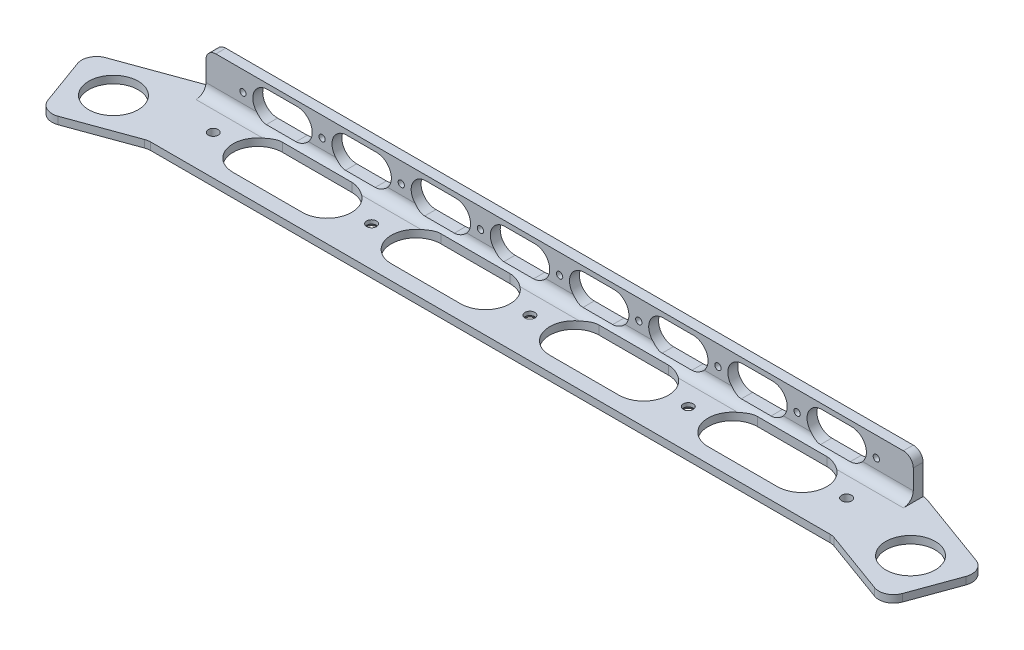
SolidWorks part; units mm, degrees
material "6061-T6 (SS)"
ref_plane "Front Plane" through (0, 0, 0) normal (0, 0, 1) x (1, 0, 0)
ref_plane "Top Plane" through (0, 0, 0) normal (0, 1, 0) x (1, 0, 0)
ref_plane "Right Plane" through (0, 0, 0) normal (1, 0, 0) x (0, 0, -1)
sketch "Sketch1" plane through (0, 0, 0) normal (0, 1, 0) x (1, 0, 0)
  line L0 (-230.1782, 50.2256) -> (-279.3199, 32.3395)
  line L1 (-217.9631, 0) -> (217.9631, 0)
  line L2 (226.9205, 50.8) -> (-226.9205, 50.8)
  line L3 (261.9453, -15.3969) -> (221.2208, -0.5744)
  line L4 (285.0127, 20.1311) -> (274.1536, -9.7041)
  line L5 (-285.0127, 20.1311) -> (-274.1536, -9.7041)
  line L6 (-261.9453, -15.3969) -> (-221.2208, -0.5744)
  line L7 (0, 50.8) -> (0, 0) construction
  line L8 (230.1782, 50.2256) -> (279.3199, 32.3395)
  arc A0 (-221.2208, -0.5744) -> (-217.9631, 0) centre (-217.9631, -9.525) cw
  arc A1 (-230.1782, 50.2256) -> (-226.9205, 50.8) centre (-226.9205, 41.275) cw
  arc A2 (-279.3199, 32.3395) -> (-285.0127, 20.1311) centre (-276.0622, 23.3889) ccw
  arc A3 (-274.1536, -9.7041) -> (-261.9453, -15.3969) centre (-265.203, -6.4464) ccw
  arc A4 (274.1536, -9.7041) -> (261.9453, -15.3969) centre (265.203, -6.4464) cw
  arc A5 (279.3199, 32.3395) -> (285.0127, 20.1311) centre (276.0622, 23.3889) cw
  arc A6 (230.1782, 50.2256) -> (226.9205, 50.8) centre (226.9205, 41.275) ccw
  arc A7 (221.2208, -0.5744) -> (217.9631, 0) centre (217.9631, -9.525) ccw
  point P11 (-228.6, 50.8)
  point P29 (228.6, 50.8)
  dimension "D3" = 9.525
  dimension "D1" = 50.8
  dimension "D2" = 20
  dimension "D4" = 63.5
  dimension "D5" = 228.6
  dimension "D6" = 50.8
extrude "Boss-Extrude1" add sketch "Sketch1" along normal blind 4.7752
sketch "Sketch2" plane through (0, 4.7752, 0) normal (0, 1, 0) x (1, 0, 0)
  line L0 (0, 50.8) -> (0, 0) construction
  line L3 (226.9205, 50.8) -> (-226.9205, 50.8) construction
  circle A0 centre (0, 25.4) radius 3.175
  circle A1 centre (-101.6, 25.4) radius 3.175
  circle A2 centre (101.6, 25.4) radius 3.175
  circle A3 centre (203.2, 25.4) radius 3.175
  circle A4 centre (-203.2, 25.4) radius 3.175
  point P4 (0, 25.4)
  dimension "D1" = 101.6
  dimension "D2" = 101.6
  dimension "D4" = 6.35
  dimension "D3" = 101.6
  dimension "D5" = 101.6
extrude "Cut-Extrude1" cut sketch "Sketch2" against normal through all
sketch "Sketch3" plane through (0, 4.7752, 0) normal (0, 1, 0) x (1, 0, 0)
  line L1 (-226.9205, 50.8) -> (226.9205, 50.8)
  line L2 (-226.9205, 50.8) -> (-226.9205, 44.45)
  line L3 (-226.9205, 44.45) -> (226.9205, 44.45)
  line L4 (226.9205, 50.8) -> (226.9205, 44.45)
  dimension "D1" = 6.35
extrude "Boss-Extrude2" add sketch "Sketch3" along normal blind 25.4
fillet "Fillet1" radius 6.35 1 edges at (0, 4.7752, -44.45)
sketch "Sketch4" plane through (0, 0, -50.8) normal (0, 0, -1) x (-1, 0, 0)
  line L0 (-226.9205, 17.4625) -> (226.9205, 17.4625) construction
  line L1 (-226.9205, 30.1752) -> (-226.9205, 4.7752) construction
  line L2 (226.9205, 30.1752) -> (226.9205, 4.7752) construction
  line L3 (-226.9205, 0) -> (226.9205, 0) construction
  dimension "D1" = 17.4625
hole_wizard "#10-32 Tapped Hole1" positions "Sketch6" profile "Sketch7" tap size "#10-32" standard "Ansi Inch" end condition up to next
sketch "Sketch6" plane through (0, 0, -50.8) normal (0, 0, -1) x (-1, 0, 0)
  line L0 (-226.9205, 17.4625) -> (226.9205, 17.4625) construction
  point P0 (0, 17.4625)
sketch "Sketch7" plane through (0, 17.4625, -50.8) normal (1, 0, 0) x (0, 1, 0)
  line L0 (0, 0) -> (0, 66.7714)
  line L1 (0, 66.7714) -> (2.0193, 66.7714)
  line L2 (2.0193, 66.7714) -> (2.0193, 0)
  line L5 (2.0193, 0) -> (0, 0)
  line L11 (0, -6.35) -> (0, 107.95) construction
  dimension "Thru Tap Drill Dia." = 4.0386
  dimension "Thru Tap Drill Depth" = 66.7714
cosmetic thread "Hole Thread1"
pattern_linear "LPattern1" count 5 spacing 50.8 along (-1, 0, 0) count 5 spacing 50.8 along (1, 0, 0) of "#10-32 Tapped Hole1"
sketch "Sketch9" plane through (0, 0, -50.8) normal (0, 0, -1) x (-1, 0, 0)
  line L0 (-226.9205, 17.4625) -> (226.9205, 17.4625) construction
  line L1 (-226.9205, 30.1752) -> (-226.9205, 4.7752) construction
  line L2 (226.9205, 30.1752) -> (226.9205, 4.7752) construction
  line L3 (-226.9205, 0) -> (226.9205, 0) construction
  line L4 (168.275, 17.4625) -> (187.325, 17.4625) construction
  line L5 (168.275, 26.9875) -> (187.325, 26.9875)
  line L6 (168.275, 7.9375) -> (187.325, 7.9375)
  arc A0 (168.275, 26.9875) -> (168.275, 7.9375) centre (168.275, 17.4625) ccw
  arc A1 (187.325, 7.9375) -> (187.325, 26.9875) centre (187.325, 17.4625) ccw
  circle A2 centre (203.2, 17.4625) radius 2.0193 construction
  point P10 (177.8, 17.4625)
  dimension "D3" = 19.05
  dimension "D2" = 9.525
  dimension "D1" = 17.4625
  dimension "D4" = 25.4
extrude "Cut-Extrude2" cut sketch "Sketch9" against normal up to next
pattern_linear "LPattern2" count 8 spacing 50.8 along (1, 0, 0) of "Cut-Extrude2"
fillet "Fillet2" radius 6.35 2 edges at (226.9205, 30.1752, -47.625) (-226.9205, 30.1752, -47.625)
sketch "Sketch10" plane through (0, 0, 0) normal (0, -1, 0) x (1, 0, 0)
  line L0 (-261.9453, 15.3969) -> (-221.2208, 0.5744) construction
  line L1 (-285.0127, -20.1311) -> (-274.1536, 9.7041) construction
  line L2 (-217.9631, 0) -> (217.9631, 0) construction
  circle A0 centre (-255.715, -13.9008) radius 15.875
  circle A1 centre (-174.625, -25.4) radius 15.875
  circle A3 centre (-130.175, -25.4) radius 15.875
  circle A4 centre (-203.2, -25.4) radius 3.175 construction
  circle A6 centre (-28.575, -25.4) radius 15.875
  circle A7 centre (-73.025, -25.4) radius 15.875
  dimension "D1" = 31.75
  dimension "D2" = 25.4
  dimension "D3" = 25.4
  dimension "D4" = 44.45
  dimension "D5" = 28.575
  dimension "D6" = 25.4
  dimension "D8" = 57.15
  dimension "D7" = 2
extrude "Cut-Extrude3" cut sketch "Sketch10" against normal up to next
mirror "Mirror1" about plane through (0, 0, 0) normal (1, 0, 0) of "Cut-Extrude3"
hole_wizard "CSK for #10 Flat Head Socket Cap Screw1" positions "Sketch12" profile "Sketch11" countersink size "#10" standard "Ansi Inch" end condition through all
sketch "Sketch12" plane through (0, 0, 0) normal (0, -1, 0) x (1, 0, 0)
  point P0 (101.6, -25.4)
  point P1 (0, -25.4)
  point P5 (-101.6, -25.4)
sketch "Sketch11" plane through (101.6, 0, -25.4) normal (1, 0, 0) x (0, 0, -1)
  line L0 (0, 0) -> (0, 30.1752)
  line L1 (0, 30.1752) -> (2.5527, 30.1752)
  line L2 (2.5527, 30.1752) -> (2.5527, 3.068)
  line L3 (2.5527, 3.068) -> (5.2197, 0)
  line L5 (5.2197, 0) -> (0, 0)
  line L6 (-2.5527, 3.068) -> (-5.2197, 0) construction
  line L11 (0, -6.35) -> (0, 107.95) construction
  dimension "Thru Hole Dia." = 5.1054
  dimension "Thru Hole Depth" = 30.1752
  dimension "Near C'Sink Dia." = 10.4394
  dimension "Near C'Sink Angle" = 82
sketch "Sketch17" plane through (0, 0, 0) normal (0, -1, 0) x (1, 0, 0)
  line L0 (-174.625, -9.525) -> (-130.175, -9.525)
  line L1 (-174.625, -41.275) -> (-130.175, -41.275)
  circle A2 centre (-174.625, -25.4) radius 15.875 construction
  circle A3 centre (-130.175, -25.4) radius 15.875 construction
  arc A4 (-174.625, -9.525) -> (-174.625, -41.275) centre (-174.625, -25.4) ccw
  arc A5 (-130.175, -41.275) -> (-130.175, -9.525) centre (-130.175, -25.4) ccw
extrude "Cut-Extrude4" cut sketch "Sketch17" against normal up to next
pattern_linear "LPattern3" count 4 spacing 101.6 along (1, 0, 0) of "Cut-Extrude4"
